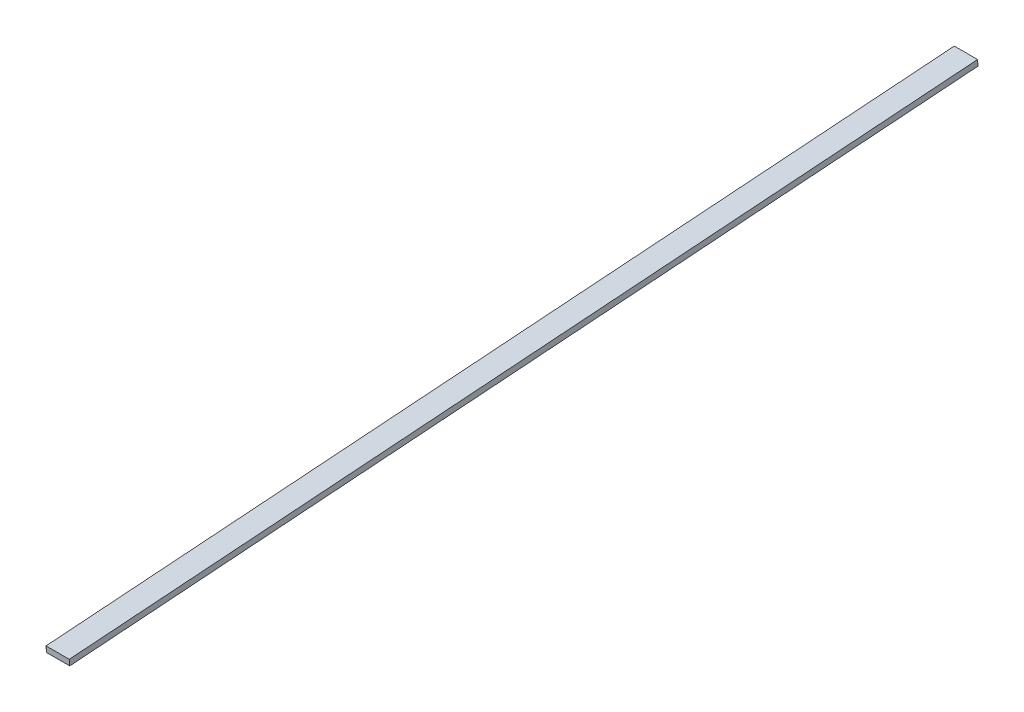
SolidWorks part; units mm, degrees
material "Spruce"
ref_plane "Front Plane" through (0, 0, 0) normal (0, 0, 1) x (1, 0, 0)
ref_plane "Top Plane" through (0, 0, 0) normal (0, 1, 0) x (1, 0, 0)
ref_plane "Right Plane" through (0, 0, 0) normal (1, 0, 0) x (0, 0, -1)
sketch "Sketch3" plane through (238.5092, 0, 0) normal (1, 0, 0) x (0, 0, -1)
  line L0 (-1497.6062, 367.9944) -> (-1500.7812, 367.7662) construction
  line L1 (-1497.6062, 367.9944) -> (-1500.7812, 367.7662)
  line L2 (-776.8812, 419.8105) -> (-780.0562, 419.5822) construction
  line L3 (-776.8812, 419.8105) -> (-780.0562, 419.5822)
  line L4 (-1497.6062, 367.9944) -> (-780.0562, 419.5822)
  line L5 (-1500.7812, 367.7662) -> (-1501.1227, 372.5164)
  line L6 (-1501.1227, 372.5164) -> (-777.2227, 424.5607)
  line L7 (-777.2227, 424.5607) -> (-776.8812, 419.8105)
  dimension "D1" = 4.7625
extrude "Boss-Extrude1" add sketch "Sketch3" along normal up to surface (18.542 mm away)
